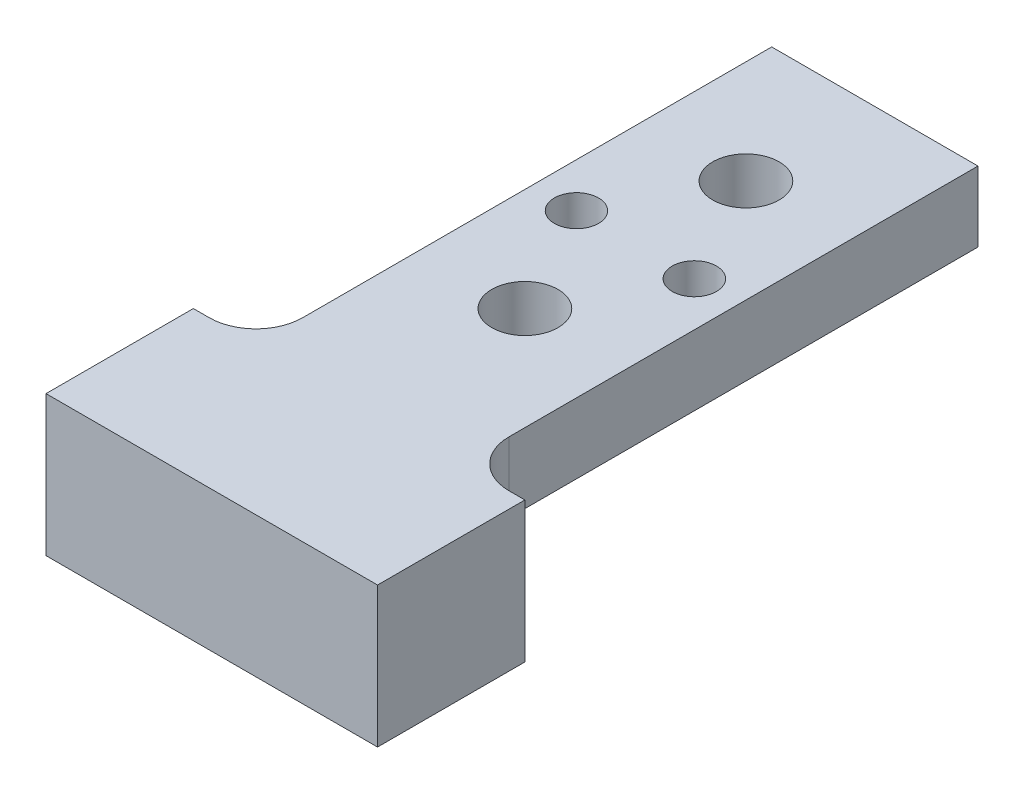
SolidWorks part; units mm, degrees
material "A2 (CLEAN GROUND)"
ref_plane "Front/Back" through (0, 0, 0) normal (0, 0, 1) x (1, 0, 0)
ref_plane "Top/Bottom" through (0, 0, 0) normal (0, 1, 0) x (1, 0, 0)
ref_plane "Right/Left" through (0, 0, 0) normal (1, 0, 0) x (0, 0, -1)
sketch "Sketch2" plane through (0, 0, 0) normal (0, 1, 0) x (1, 0, 0)
  line L1 (-22.5, 45) -> (22.5, 45)
  line L2 (-22.5, 45) -> (-22.5, -45)
  line L3 (-22.5, -45) -> (22.5, -45)
  line L4 (22.5, 45) -> (22.5, -45)
  line L5 (0, 0) -> (22.5, 0) construction
  line L6 (0, 0) -> (0, 45) construction
  dimension "D1" = 45
  dimension "D2" = 90
extrude "Extrude2" add sketch "Sketch2" along normal mid plane 19.05
sketch "Sketch4" plane through (22.5, 0, 0) normal (1, 0, 0) x (0, 0, -1)
  line L0 (-45, 9.525) -> (-45, -9.525) construction
  line L1 (45, -9.525) -> (-25, -9.525)
  line L2 (45, -9.525) -> (45, 0)
  line L3 (45, 0) -> (-25, 0)
  line L4 (-25, -9.525) -> (-25, 0)
  dimension "D1" = 20
extrude "Cut-Extrude1" cut sketch "Sketch4" against normal through all
sketch "Sketch5" plane through (0, 9.525, 0) normal (0, 1, 0) x (1, 0, 0)
  line L0 (-22.5, -25) -> (22.5, -25) construction
  line L1 (-22.5, 45) -> (-14, 45)
  line L2 (-22.5, 45) -> (-22.5, -25)
  line L3 (-22.5, -25) -> (-14, -25)
  line L4 (-14, 45) -> (-14, -25)
  line L5 (22.5, 45) -> (14, 45)
  line L6 (22.5, 45) -> (22.5, -25)
  line L7 (22.5, -25) -> (14, -25)
  line L8 (14, 45) -> (14, -25)
  dimension "D1" = 8.5
extrude "Cut-Extrude2" cut sketch "Sketch5" against normal through all
fillet "Fillet1" radius 6.35 2 edges at (-14, 4.7625, 25) (14, 4.7625, 25)
hole_wizard "Ø6.0 (6) Diameter Hole1" positions "Sketch7" profile "Sketch6" hole size "Ø6.0" standard "Ansi Metric" end condition through all
sketch "Sketch7" plane through (0, 9.525, 0) normal (0, 1, 0) x (-1, 0, 0)
  point P1 (-8, -12.5)
  point P4 (8, -12.5)
sketch "Sketch6" plane through (8, 9.525, -12.5) normal (1, 0, 0) x (0, 0, 1)
  line L0 (0, 0) -> (0, 19.05)
  line L1 (0, 19.05) -> (3, 19.05)
  line L2 (3, 19.05) -> (3, 0)
  line L5 (3, 0) -> (0, 0)
  line L11 (0, -6.35) -> (0, 107.95) construction
  dimension "Thru Hole Dia." = 6
  dimension "Thru Hole Depth" = 19.05
hole_wizard "M8 Clearance Hole1" positions "Sketch9" profile "Sketch8" hole size "M8" standard "_*ATS Preferred Ansi METRIC" end condition through all
sketch "Sketch9" plane through (0, 9.525, 0) normal (0, 1, 0) x (-1, 0, 0)
  point P0 (0, -27.5)
  point P1 (0, 2.5)
sketch "Sketch8" plane through (0, 9.525, -27.5) normal (1, 0, 0) x (0, 0, 1)
  line L0 (0, 0) -> (0, 19.05)
  line L1 (0, 19.05) -> (4.5, 19.05)
  line L2 (4.5, 19.05) -> (4.5, 0)
  line L5 (4.5, 0) -> (0, 0)
  line L11 (0, -6.35) -> (0, 107.95) construction
  dimension "Thru Hole Dia." = 9
  dimension "Thru Hole Depth" = 19.05
